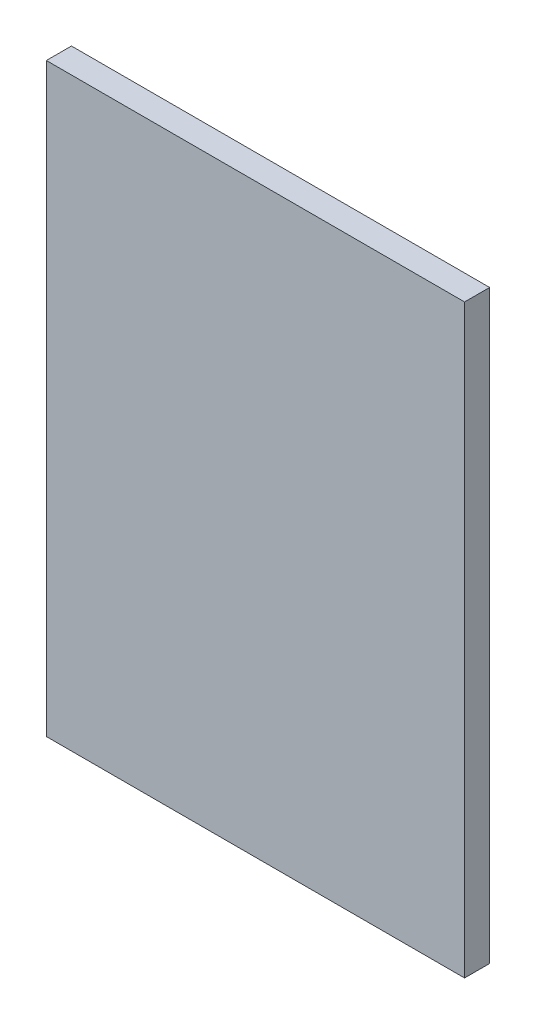
SolidWorks part; units mm, degrees
ref_plane "Спереди" through (0, 0, 0) normal (0, 0, 1) x (1, 0, 0)
ref_plane "Сверху" through (0, 0, 0) normal (0, 1, 0) x (1, 0, 0)
ref_plane "Справа" through (0, 0, 0) normal (1, 0, 0) x (0, 0, -1)
sketch "Эскиз1" plane through (0, 0, 0) normal (0, 0, 1) x (1, 0, 0)
  line L0 (0, 17.5) -> (0, 0) construction
  line L1 (-12.5, 17.5) -> (12.5, 17.5)
  line L2 (-12.5, 17.5) -> (-12.5, -17.5)
  line L3 (-12.5, -17.5) -> (12.5, -17.5)
  line L4 (12.5, 17.5) -> (12.5, -17.5)
  line L5 (0, 0) -> (12.5, 0) construction
  dimension "D1" = 25
  dimension "D2" = 35
extrude "Вытянуть1" add sketch "Эскиз1" along normal blind 1.5
sketch "Эскиз2" plane through (0, -17.5, 0) normal (0, -1, 0) x (1, 0, 0)
  line L0 (0, 0) -> (0, 1.5) construction
  line L1 (-12.5, 1.5) -> (12.5, 1.5) construction
